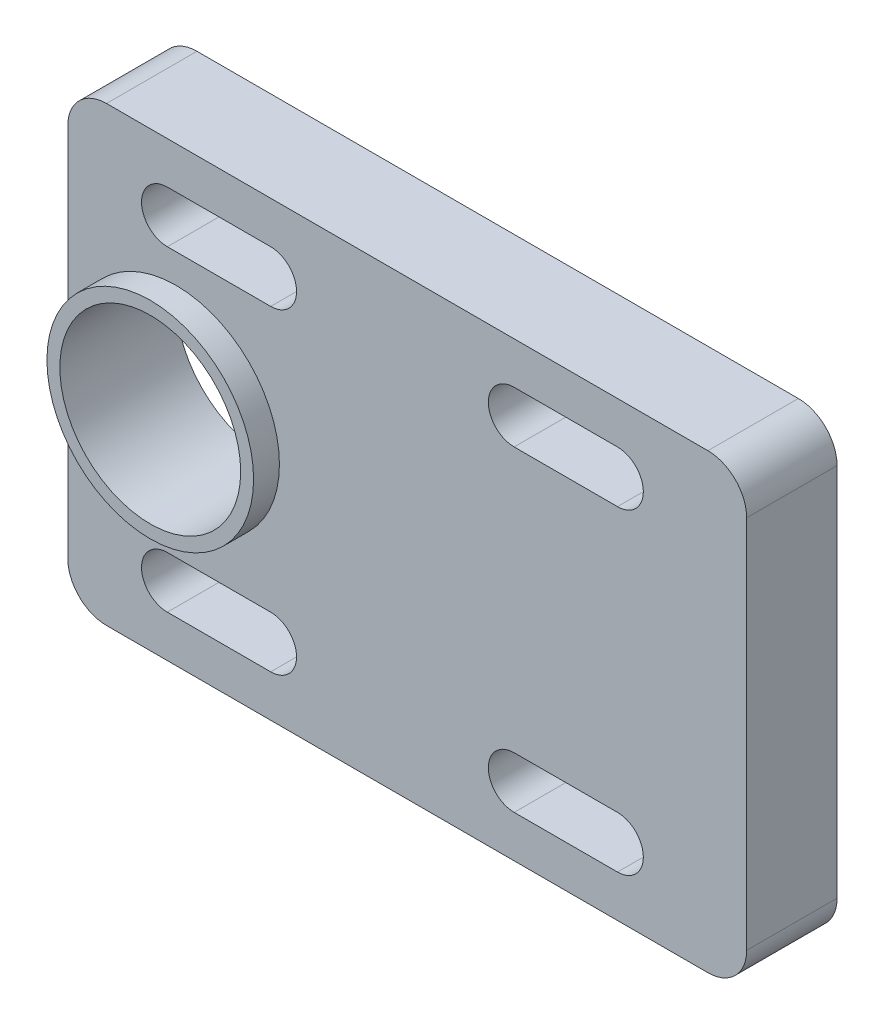
SolidWorks part; units mm, degrees
ref_plane "Front Plane" through (0, 0, 0) normal (0, 0, 1) x (1, 0, 0)
ref_plane "Top Plane" through (0, 0, 0) normal (0, 1, 0) x (1, 0, 0)
ref_plane "Right Plane" through (0, 0, 0) normal (1, 0, 0) x (0, 0, -1)
sketch "Sketch1" plane through (0, 0, 0) normal (0, 0, 1) x (1, 0, 0)
  line L0 (-178.3681, 12.25) -> (-186.3681, 12.25) construction
  line L1 (-151.5213, -12.25) -> (-159.5213, -12.25) construction
  line L2 (-191.0782, -17.5) -> (-144.5213, -17.5)
  line L3 (-194.0782, -14.5) -> (-194.0782, 14.5)
  line L4 (-191.0782, 17.5) -> (-144.5213, 17.5)
  line L5 (-141.5213, -14.5) -> (-141.5213, 14.5)
  line L6 (-178.3681, 10.25) -> (-186.3681, 10.25)
  line L7 (-178.3681, 14.25) -> (-186.3681, 14.25)
  line L8 (-151.5213, -14.25) -> (-159.5213, -14.25)
  line L9 (-151.5213, -10.25) -> (-159.5213, -10.25)
  line L10 (-151.5213, 12.25) -> (-159.5213, 12.25) construction
  line L11 (-151.5213, 10.25) -> (-159.5213, 10.25)
  line L12 (-151.5213, 14.25) -> (-159.5213, 14.25)
  line L13 (-178.3681, -12.25) -> (-186.3681, -12.25) construction
  line L14 (-178.3681, -14.25) -> (-186.3681, -14.25)
  line L15 (-178.3681, -10.25) -> (-186.3681, -10.25)
  arc A1 (-151.5213, -14.25) -> (-151.5213, -10.25) centre (-151.5213, -12.25) ccw
  arc A2 (-159.5213, -10.25) -> (-159.5213, -14.25) centre (-159.5213, -12.25) ccw
  arc A3 (-151.5213, 10.25) -> (-151.5213, 14.25) centre (-151.5213, 12.25) ccw
  arc A4 (-159.5213, 14.25) -> (-159.5213, 10.25) centre (-159.5213, 12.25) ccw
  arc A6 (-178.3681, 10.25) -> (-178.3681, 14.25) centre (-178.3681, 12.25) ccw
  circle A7 centre (-176.5782, 0) radius 17.5 construction
  circle A8 centre (-159.5213, 12.25) radius 3.5 construction
  circle A9 centre (-159.5213, -12.25) radius 3.5 construction
  arc A10 (-194.0782, 14.5) -> (-191.0782, 17.5) centre (-191.0782, 14.5) cw
  arc A11 (-191.0782, -17.5) -> (-194.0782, -14.5) centre (-191.0782, -14.5) cw
  arc A12 (-144.5213, -17.5) -> (-141.5213, -14.5) centre (-144.5213, -14.5) ccw
  arc A13 (-144.5213, 17.5) -> (-141.5213, 14.5) centre (-144.5213, 14.5) cw
  arc A14 (-186.3681, 14.25) -> (-186.3681, 10.25) centre (-186.3681, 12.25) ccw
  arc A15 (-178.3681, -14.25) -> (-178.3681, -10.25) centre (-178.3681, -12.25) ccw
  arc A16 (-186.3681, -10.25) -> (-186.3681, -14.25) centre (-186.3681, -12.25) ccw
  circle A17 centre (-186.3681, -12.25) radius 1.5 construction
  circle A18 centre (-186.3681, 12.25) radius 1.5 construction
  circle A19 centre (-159.5213, 12.25) radius 1.5 construction
  circle A20 centre (-159.5213, -12.25) radius 2 construction
  circle A21 centre (-185.6928, 0) radius 7
  arc A22 (-185.6928, -3.5) -> (-185.6928, 3.5) centre (-185.6928, 0) ccw construction
  point P5 (-141.5213, 0)
  point P6 (-182.3681, 12.25)
  point P12 (-155.5213, -12.25)
  point P17 (-155.5213, 12.25)
  point P25 (-182.3681, -12.25)
  dimension "D1" = 35
  dimension "D2" = 1.5
  dimension "D4" = 3
  dimension "D5" = 2
  dimension "D7" = 29
  dimension "D8" = 14
  dimension "D3" = 8
  dimension "D6" = 10
extrude "Boss-Extrude1" add sketch "Sketch1" along normal blind 9 contours L12 A8 L11 A4 | A7 | A10 L3 A7 L4 | A11 L2 A7 L3 | A9 A7 L2 | L9 A9 L8 A2
sketch "Sketch2" plane through (0, 0, 9) normal (0, 0, 1) x (1, 0, 0)
  circle A2 centre (-185.6928, 0) radius 8
  circle A4 centre (-185.6928, 0) radius 7 construction
  arc M2 (-178.3681, 14.25) -> (-178.3681, 10.25) centre (-178.3681, 12.25) cw
  line M3 (-178.3681, 10.25) -> (-186.3681, 10.25)
  arc M4 (-186.3681, 10.25) -> (-186.3681, 14.25) centre (-186.3681, 12.25) cw
  line M5 (-186.3681, 14.25) -> (-178.3681, 14.25)
  arc M6 (-194.0782, -14.5) -> (-191.0782, -17.5) centre (-191.0782, -14.5) ccw
  line M7 (-191.0782, -17.5) -> (-144.5213, -17.5)
  arc M8 (-144.5213, -17.5) -> (-141.5213, -14.5) centre (-144.5213, -14.5) ccw
  line M9 (-141.5213, -14.5) -> (-141.5213, 14.5)
  arc M10 (-141.5213, 14.5) -> (-144.5213, 17.5) centre (-144.5213, 14.5) ccw
  line M11 (-144.5213, 17.5) -> (-191.0782, 17.5)
  arc M12 (-191.0782, 17.5) -> (-194.0782, 14.5) centre (-191.0782, 14.5) ccw
  line M13 (-194.0782, 14.5) -> (-194.0782, -14.5)
  line M14 (-186.3681, -10.25) -> (-178.3681, -10.25)
  arc M15 (-178.3681, -10.25) -> (-178.3681, -14.25) centre (-178.3681, -12.25) cw
  line M16 (-178.3681, -14.25) -> (-186.3681, -14.25)
  arc M17 (-186.3681, -14.25) -> (-186.3681, -10.25) centre (-186.3681, -12.25) cw
  arc M18 (-159.5213, -14.25) -> (-159.5213, -10.25) centre (-159.5213, -12.25) cw
  line M19 (-159.5213, -10.25) -> (-151.5213, -10.25)
  arc M20 (-151.5213, -10.25) -> (-151.5213, -14.25) centre (-151.5213, -12.25) cw
  line M21 (-151.5213, -14.25) -> (-159.5213, -14.25)
  line M22 (-159.5213, 14.25) -> (-151.5213, 14.25)
  arc M23 (-151.5213, 14.25) -> (-151.5213, 10.25) centre (-151.5213, 12.25) cw
  line M24 (-151.5213, 10.25) -> (-159.5213, 10.25)
  arc M25 (-159.5213, 10.25) -> (-159.5213, 14.25) centre (-159.5213, 12.25) cw
  dimension "D1" = 16
extrude "Cut-Extrude1" cut sketch "Sketch2" against normal blind 2 contours A2 M13 M6 M7 M8 M9 M10 M11 M12 M17 M14 M15 M16 M21 M18 M19 M20 M25 M22 M23 M24 M5 M2 M3 M4
